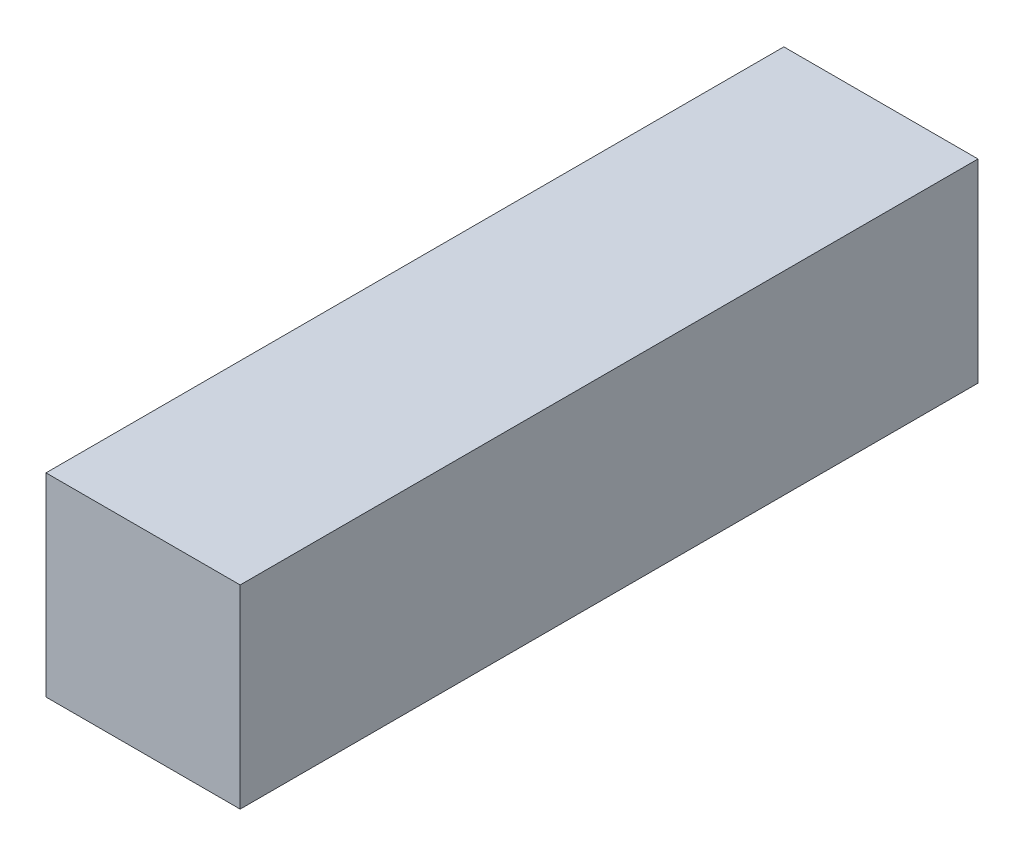
SolidWorks part; units mm, degrees
ref_plane "Front Plane" through (0, 0, 0) normal (0, 0, 1) x (1, 0, 0)
ref_plane "Top Plane" through (0, 0, 0) normal (0, 1, 0) x (1, 0, 0)
ref_plane "Right Plane" through (0, 0, 0) normal (1, 0, 0) x (0, 0, -1)
sketch "Sketch1" plane through (0, 0, 0) normal (0, 0, 1) x (1, 0, 0)
  line L1 (0, 0) -> (31.75, 0)
  line L2 (0, 0) -> (0, 31.75)
  line L3 (0, 31.75) -> (31.75, 31.75)
  line L4 (31.75, 0) -> (31.75, 31.75)
  dimension "D1" = 31.75
  dimension "D2" = 31.75
extrude "Extrude1" add sketch "Sketch1" along normal blind 120.65
